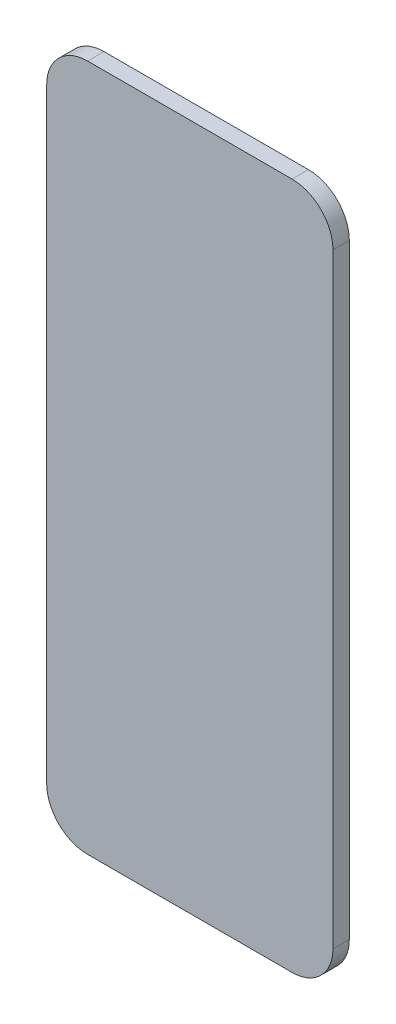
SolidWorks part; units mm, degrees
ref_plane "Front Plane" through (0, 0, 0) normal (0, 0, 1) x (1, 0, 0)
ref_plane "Top Plane" through (0, 0, 0) normal (0, 1, 0) x (1, 0, 0)
ref_plane "Right Plane" through (0, 0, 0) normal (1, 0, 0) x (0, 0, -1)
sketch "Sketch1" plane through (0, 0, 0) normal (0, 0, 1) x (1, 0, 0)
  line L1 (0, 0) -> (700, 0)
  line L2 (0, 0) -> (0, 1680)
  line L3 (0, 1680) -> (700, 1680)
  line L4 (700, 0) -> (700, 1680)
  dimension "D1" = 700
  dimension "D2" = 1680
extrude "Boss-Extrude1" add sketch "Sketch1" along normal blind 40
fillet "Fillet1" radius 100 4 edges at (700, 0, 20) (0, 0, 20) (0, 1680, 20) (700, 1680, 20)
